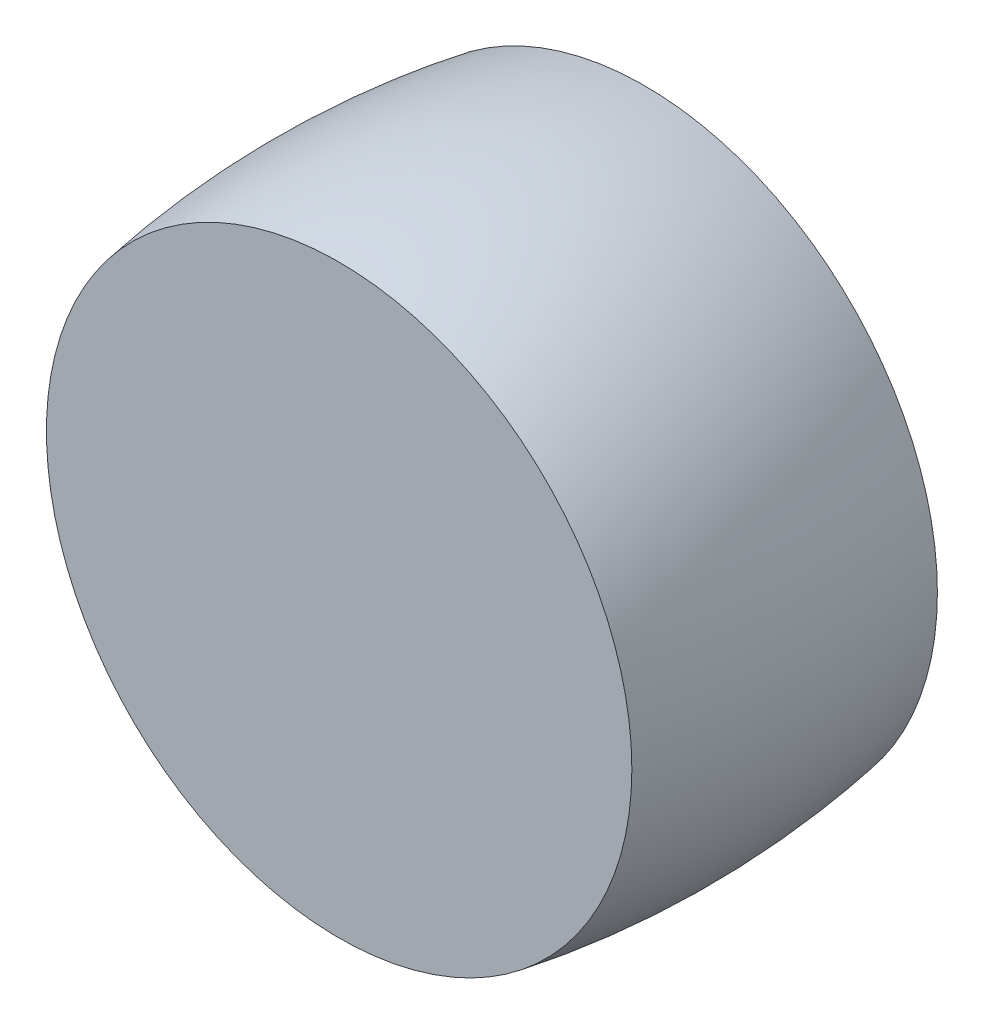
SolidWorks part; units mm, degrees
ref_plane "前视基准面" through (0, 0, 0) normal (0, 0, 1) x (1, 0, 0)
ref_plane "上视基准面" through (0, 0, 0) normal (0, 1, 0) x (1, 0, 0)
ref_plane "右视基准面" through (0, 0, 0) normal (1, 0, 0) x (0, 0, -1)
other "Configuration Table"
sketch "草图2" plane through (0, 0, 0) normal (0, 1, 0) x (1, 0, 0)
  line L0 (0, -57.5641) -> (0, 58.4653) construction
  line L6 (0, -20) -> (38.3216, -20)
  line L7 (0, -20) -> (0, 20)
  line L8 (0, 20) -> (38.3216, 20)
  arc A0 (38.3216, -20) -> (38.3216, 20) centre (-80, 0) ccw
  point P4 (40, 0)
  point P7 (0, 0)
  dimension "D1" = 40
  dimension "D2" = 40
revolve "旋转1" add sketch "草图2" angle 360 about L0
